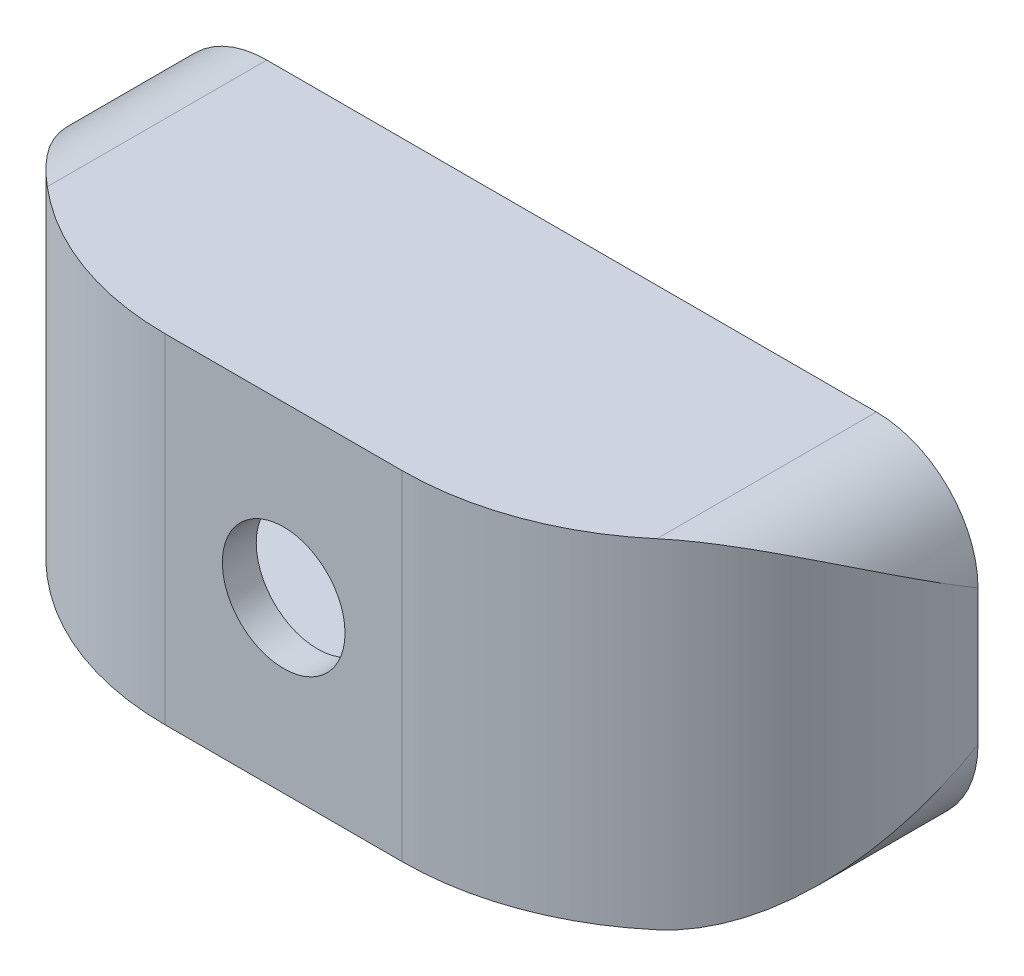
SolidWorks part; units mm, degrees
ref_plane "Front Plane" through (0, 0, 0) normal (0, 0, 1) x (1, 0, 0)
ref_plane "Top Plane" through (0, 0, 0) normal (0, 1, 0) x (1, 0, 0)
ref_plane "Right Plane" through (0, 0, 0) normal (1, 0, 0) x (0, 0, -1)
sketch "Sketch3" plane through (0, 0, 0) normal (0, 1, 0) x (1, 0, 0)
  line L0 (-76.2, 0) -> (76.2, 0)
  line L1 (-22.225, -53.975) -> (22.225, -53.975)
  arc A0 (22.225, -53.975) -> (76.2, 0) centre (22.225, 0) ccw
  arc A1 (-22.225, -53.975) -> (-76.2, 0) centre (-22.225, 0) cw
  point P6 (0, -53.975)
  dimension "D1" = 44.45
  dimension "D2" = 53.975
extrude "Boss-Extrude2" add sketch "Sketch3" along normal up to surface (44.45 mm away) and the other way up to surface (19.05 mm away)
sketch "Sketch4" plane through (0, 0, 53.975) normal (0, 0, 1) x (1, 0, 0)
  line L0 (-76.2, 0) -> (-76.2, 25.4) construction
  line L1 (57.15, -19.05) -> (-57.15, -19.05) construction
  line L2 (76.2, 25.4) -> (76.2, 0) construction
  line L3 (-57.15, 44.45) -> (57.15, 44.45) construction
  line L4 (-76.2, 0) -> (-76.2, 25.4)
  line L5 (57.15, -19.05) -> (-57.15, -19.05)
  line L6 (76.2, 25.4) -> (76.2, 0)
  line L7 (-57.15, 44.45) -> (57.15, 44.45)
  arc A0 (-57.15, 44.45) -> (-76.2, 25.4) centre (-57.15, 25.4) ccw construction
  arc A1 (-76.2, 0) -> (-57.15, -19.05) centre (-57.15, 0) ccw construction
  arc A2 (57.15, -19.05) -> (76.2, 0) centre (57.15, 0) ccw construction
  arc A3 (76.2, 25.4) -> (57.15, 44.45) centre (57.15, 25.4) ccw construction
  arc A4 (-57.15, 44.45) -> (-76.2, 25.4) centre (-57.15, 25.4) ccw
  arc A5 (-76.2, 0) -> (-57.15, -19.05) centre (-57.15, 0) ccw
  arc A6 (57.15, -19.05) -> (76.2, 0) centre (57.15, 0) ccw
  arc A7 (76.2, 25.4) -> (57.15, 44.45) centre (57.15, 25.4) ccw
extrude "Cut-Extrude-Thin1" cut sketch "Sketch4" against normal through all thin thin type one direction wall 12.7
shell "Shell1" thickness 6.35
sketch "Sketch5" plane through (0, 0, 53.975) normal (0, 0, 1) x (1, 0, 0)
  line L0 (-22.225, 44.45) -> (-22.225, -19.05) construction
  circle A0 centre (0, 12.7) radius 11.5
  point P5 (-22.225, 12.7)
  dimension "D1" = 23
extrude "Cut-Extrude1" cut sketch "Sketch5" against normal up to surface (6.35 mm away) up to face at (0, 12.7, 47.625)
sketch "Sketch6" plane through (0, 0, 0) normal (0, 1, 0) x (1, 0, 0)
  line L1 (-20.6375, -6.35) -> (20.6375, -6.35)
  line L2 (-20.6375, -6.35) -> (-20.6375, -50.8)
  line L3 (-20.6375, -50.8) -> (20.6375, -50.8)
  line L4 (20.6375, -6.35) -> (20.6375, -50.8)
  line L6 (-57.15, 0) -> (57.15, 0) construction
  line L7 (22.225, -53.975) -> (-22.225, -53.975) construction
  point P4 (0, -6.35)
  dimension "D1" = 44.45
  dimension "D2" = 41.275
  dimension "D3" = 6.35
  dimension "D4" = 3.175
sketch "Sketch8" plane through (0, 0, 0) normal (0, 0, -1) x (-1, 0, 0)
  line L0 (57.15, 38.1) -> (-57.15, 38.1) construction
  line L1 (-76.2, 25.4) -> (-76.2, 0) construction
  line L2 (57.15, -12.7) -> (-57.15, -12.7) construction
  line L3 (0, 29.6863) -> (0, -29.6863) construction
  line L4 (-57.15, 38.1) -> (-22.225, 38.1) construction
  line L5 (-52.3875, 28.575) -> (-42.8625, 28.575)
  line L6 (-52.3875, 28.575) -> (-52.3875, 38.1)
  line L7 (-52.3875, 38.1) -> (-42.8625, 38.1)
  line L8 (-42.8625, 28.575) -> (-42.8625, 38.1)
  line L9 (-52.3875, 28.575) -> (-42.8625, 38.1) construction
  line L10 (-52.3875, 38.1) -> (-42.8625, 28.575) construction
  line L11 (-22.225, -12.7) -> (-57.15, -12.7) construction
  line L12 (-61.9125, -3.175) -> (-52.3875, -3.175)
  line L13 (-61.9125, -3.175) -> (-61.9125, -12.7)
  line L14 (-61.9125, -12.7) -> (-52.3875, -12.7)
  line L15 (-52.3875, -3.175) -> (-52.3875, -12.7)
  line L16 (-61.9125, -3.175) -> (-52.3875, -12.7) construction
  line L17 (-61.9125, -12.7) -> (-52.3875, -3.175) construction
  line L18 (52.3875, -3.175) -> (52.3875, -12.7)
  line L19 (61.9125, -12.7) -> (52.3875, -12.7)
  line L20 (61.9125, -3.175) -> (61.9125, -12.7)
  line L21 (61.9125, -3.175) -> (52.3875, -3.175)
  line L22 (52.3875, 28.575) -> (42.8625, 28.575)
  line L23 (42.8625, 28.575) -> (42.8625, 38.1)
  line L24 (52.3875, 38.1) -> (42.8625, 38.1)
  line L25 (52.3875, 28.575) -> (52.3875, 38.1)
  circle A0 centre (-47.625, 33.3375) radius 1.5
  circle A3 centre (-57.15, -7.9375) radius 1.5
  circle A4 centre (57.15, -7.9375) radius 1.5
  circle A5 centre (47.625, 33.3375) radius 1.5
  dimension "D1" = 3
  dimension "D2" = 4.7625
  dimension "D3" = 28.575
  dimension "D4" = 4.7625
  dimension "D5" = 19.05
  dimension "D6" = 9.525
  dimension "D7" = 9.525
extrude "Boss-Extrude3" add sketch "Sketch8" against normal up to next
fillet "Fillet1" radius 2.54 8 edges at (-52.3875, 28.575, 18.428) (-42.8625, 28.575, 21.4606) (-61.9125, -3.175, 13.1629) (-52.3875, -3.175, 18.428) (61.9125, -3.175, 13.1629) (52.3875, -3.175, 18.428) (52.3875, 28.575, 18.428) (42.8625, 28.575, 21.4606)
